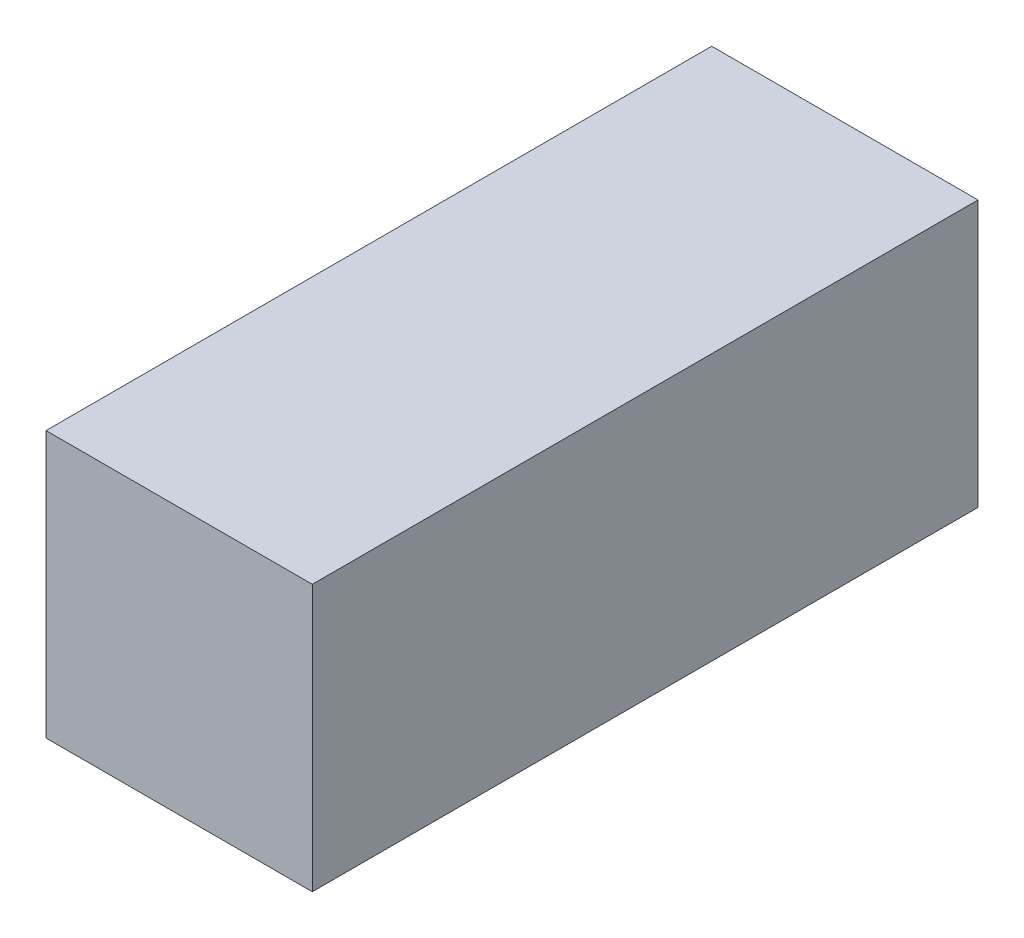
SolidWorks part; units mm, degrees
ref_plane "正面" through (0, 0, 0) normal (0, 0, 1) x (1, 0, 0)
ref_plane "平面" through (0, 0, 0) normal (0, 1, 0) x (1, 0, 0)
ref_plane "右側面" through (0, 0, 0) normal (1, 0, 0) x (0, 0, -1)
sketch "ｽｹｯﾁ1" plane through (0, 0, 0) normal (0, 0, 1) x (1, 0, 0)
  line L1 (0, 0) -> (200, 0)
  line L2 (0, 0) -> (0, 200)
  line L3 (0, 200) -> (200, 200)
  line L4 (200, 0) -> (200, 200)
extrude "ﾎﾞｽ - 押し出し1" add sketch "ｽｹｯﾁ1" along normal blind 500
